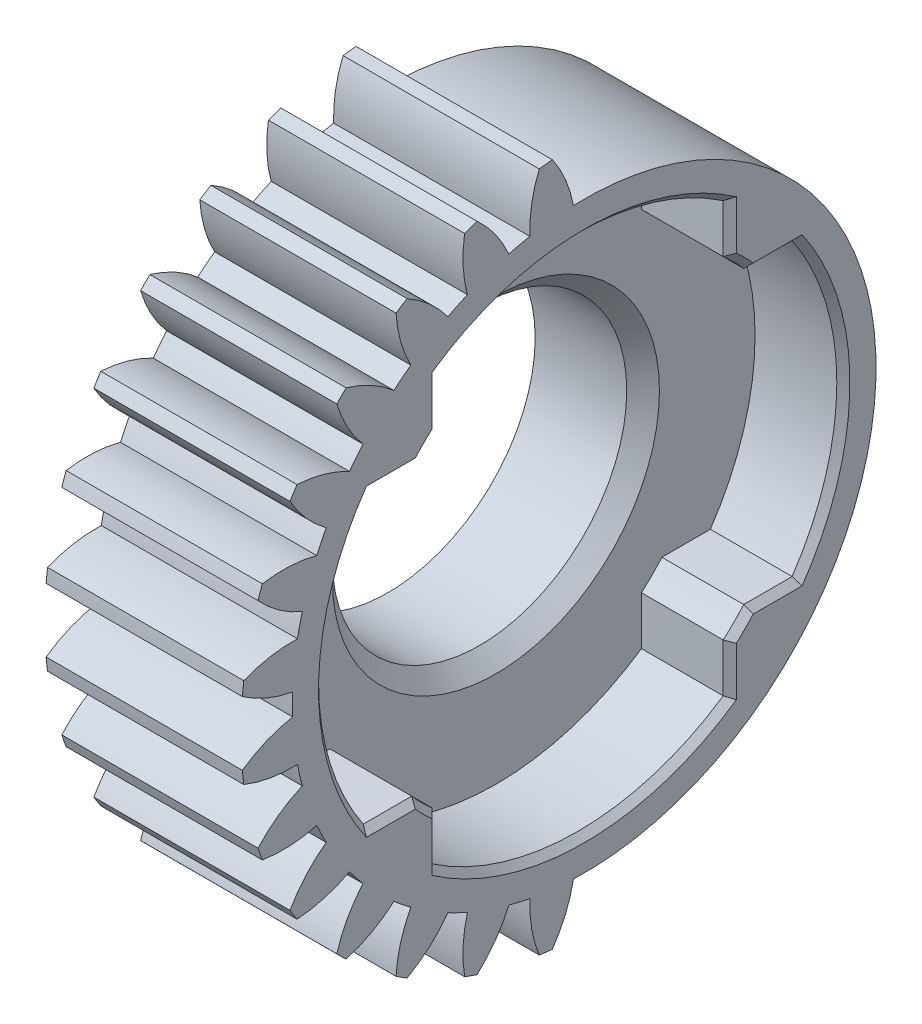
SolidWorks part; units mm, degrees
ref_plane "Plane1" through (0, 0, 0) normal (0, 0, 1) x (1, 0, 0)
ref_plane "Plane2" through (0, 0, 0) normal (0, 1, 0) x (1, 0, 0)
ref_plane "Plane3" through (0, 0, 0) normal (1, 0, 0) x (0, 0, -1)
sketch "HoldingSke" plane through (0, 0, 0) normal (0, 1, 0) x (1, 0, 0)
  line L0 (0, 0) -> (1.2614, -0.6707)
  line L1 (-15, 0) -> (100, 0) construction
  line L2 (0, 0) -> (-2.1039, 2.3779)
  line L3 (0, 0) -> (-11.863, 4.5341)
  line L4 (0, 0) -> (7.6251, 4.0544)
  line L5 (0, 0) -> (-46.8476, -17.4728)
  line L6 (0, 0) -> (-4.9738, -3.3558)
  line L7 (-2.1039, 2.3779) -> (8.6586, 51.2059)
  line L8 (-76.2, 54.61) -> (-75.7, 54.61)
  line L9 (-71.009, 38.7566) -> (-53.1078, 45.2721)
  line L10 (-76.2, 71.12) -> (104.1128, 71.12)
  line L11 (0, 0) -> (-6, 0)
  line L12 (-76.2, 101.6) -> (-76.173, 101.6)
  line L13 (24.9733, 27.94) -> (52.9518, 28.4284)
  line L14 (24.9733, 27.94) -> (24.9743, 27.94)
  line L15 (24.9733, 27.94) -> (100.4006, 29.5858)
  line L16 (-63.627, -0.7) -> (-12.827, -0.7)
  circle A0 centre (0, 0) radius 1.5
  circle A1 centre (0, 0) radius 8.924
  circle A2 centre (0, 0) radius 37.5
  circle A3 centre (0, 0) radius 1.5
  dimension "MHD" = 17.848
  dimension "Hub_dia" = 75
  dimension "Bore" = 3
  dimension "MBD" = 3
  dimension "Num_teeth" = 28
  dimension "Pitch" = 1.4286
  dimension "Overall_len" = 50
  dimension "Show_teeth" = 28
  dimension "Thickness" = 6
  dimension "OAL" = 50.0001
  dimension "T_dim" = 0.5
  dimension "Ap" = 20
  dimension "H" = 19.05
  dimension "Pitch_radius" = 180.3128
  dimension "Width" = 6
  dimension "Backlash" = 0.027
  dimension "Addendum_fac" = 1
  dimension "Dedendum_fac" = 1.25
  dimension "Clearance_fac" = 0.25
  dimension "Dedendum_add" = 0.001
  dimension "Module" = 0.7
sketch "BasProSke" plane through (0, 0, 0) normal (0, 1, 0) x (1, 0, 0)
  line L0 (-10, 0) -> (60, 0) construction
  line L1 (0, 0) -> (0, 10.5)
  line L2 (0, 0) -> (6, 0)
  line L3 (6, 0) -> (6, 10.5)
  line L4 (6, 10.5) -> (0, 10.5)
  dimension "Thickness" = 6
  dimension "Diameter" = 21
revolve "Base-Revolve" add sketch "BasProSke" angle 360 about L0
sketch "TooCutSke" plane through (0, 0, 0) normal (1, 0, 0) x (0, 0, -1)
  line L1 (0, 0) -> (0, 107) construction
  line L2 (0, 0) -> (-0.5967, 9.7818) construction
  line L3 (0, 0) -> (-2.1916, 19.4512) construction
  line L4 (-0.5967, 9.7818) -> (-1.0958, 9.7256) construction
  arc A0 (0.3305, 8.9179) -> (-0.3305, 8.9179) centre (0, 0) ccw
  arc A1 (0.9927, 10.4785) -> (-0.9927, 10.4785) centre (0, 0) ccw
  circle A2 centre (0, 0) radius 9.8 construction
  circle A3 centre (0, 0) radius 9.209 construction
  arc A4 (-0.3305, 8.9179) -> (-0.9927, 10.4785) centre (-4.1848, 8.2032) ccw
  arc A5 (0.9927, 10.4785) -> (0.3305, 8.9179) centre (4.1848, 8.2032) ccw
  dimension "Root_dia" = 17.848
  dimension "Overcut_dia" = 21.0508
  dimension "Pitch_dia" = 19.6
  dimension "Base_dia" = 18.418
  dimension "Flank_rad" = 3.92
  dimension "Half_ang" = 6.429
  dimension "Half_CT" = 0.5022
extrude "ToothCut" cut sketch "TooCutSke" along normal through all
fillet "Breaks" [suppressed] radius 0.014
fillet "RootFillets" [suppressed] radius 0.176
pattern_circular "TeethCuts" count 28 every 12.857 about axis through (-10, 0, 0) along (1, 0, 0) of "ToothCut", "RootFillets", "Breaks"
sketch "HubNeaOneSke" plane through (0, 0, 0) normal (-1, 0, 0) x (0, 0, 1)
  circle A0 centre (0, 0) radius 8.924
  dimension "Diameter" = 17.848
extrude "HubNearOne" [suppressed] add sketch "HubNeaOneSke" along normal blind 44.0001
sketch "HubNeaBotSke" plane through (0, 0, 0) normal (-1, 0, 0) x (0, 0, 1)
  circle A0 centre (0, 0) radius 8.924
  dimension "Diameter" = 17.848
extrude "HubNearBoth" [suppressed] add sketch "HubNeaBotSke" along normal blind 22
ref_plane "FarPln" through (6, 0, 0) normal (1, 0, 0) x (0, 0, -1)
sketch "HubFarSke" plane through (6, 0, 0) normal (1, 0, 0) x (0, 0, -1)
  circle A0 centre (0, 0) radius 8.924
  dimension "Diameter" = 17.848
extrude "HubFar" [suppressed] add sketch "HubFarSke" along normal blind 22
sketch "BorSke" plane through (0, 0, 0) normal (1, 0, 0) x (0, 0, -1)
  circle A0 centre (0, 0) radius 1.5
  dimension "Diameter" = 3
extrude "Bore" cut sketch "BorSke" along normal mid plane 100.0001
sketch "KeySke" plane through (0, 0, 0) normal (1, 0, 0) x (0, 0, -1)
  line L0 (-0.6, 0) -> (-0.6, 2)
  line L1 (-0.6, 2) -> (0.6, 2)
  line L2 (0.6, 2) -> (0.6, 0)
  line L3 (0, 0) -> (0, 34) construction
  line L4 (-0.6, 0) -> (0.6, 0)
  dimension "Offset" = 2
  dimension "Width" = 1.2
extrude "Keyway" [suppressed] cut sketch "KeySke" along normal mid plane 100.0001
pattern_circular "Keyway2" [suppressed] count 2 every 90 about axis through (-10, 0, 0) along (1, 0, 0)
sketch "Szkic1" plane through (6, 0, 0) normal (1, 0, 0) x (0, 0, -1)
  circle A0 centre (0, 0) radius 6.75
  dimension "D1" = 13.5
extrude "Wytnij-wyciągnięcie1" cut sketch "Szkic1" against normal blind 2.7
sketch "Szkic2" plane through (3.3, 0, 0) normal (1, 0, 0) x (0, 0, -1)
  circle A0 centre (0, 0) radius 4.5
  dimension "D1" = 9
extrude "Wytnij-wyciągnięcie2" cut sketch "Szkic2" against normal through all
sketch "Szkic3" plane through (6, 0, 0) normal (1, 0, 0) x (0, 0, -1)
  line L1 (6.5565, -4.45) -> (-6.5565, -4.45)
  line L2 (6.5565, -4.45) -> (6.5565, 4.45)
  line L3 (6.5565, 4.45) -> (-6.5565, 4.45)
  line L4 (-6.5565, -4.45) -> (-6.5565, 4.45)
  line L5 (6.5565, -4.45) -> (-6.5565, 4.45) construction
  line L6 (6.5565, 4.45) -> (-6.5565, -4.45) construction
  line L7 (4.45, -6.5565) -> (-4.45, -6.5565)
  line L8 (4.45, -6.5565) -> (4.45, 6.5565)
  line L9 (4.45, 6.5565) -> (-4.45, 6.5565)
  line L10 (-4.45, -6.5565) -> (-4.45, 6.5565)
  line L11 (4.45, -6.5565) -> (-4.45, 6.5565) construction
  line L12 (4.45, 6.5565) -> (-4.45, -6.5565) construction
  circle A0 centre (0, 0) radius 7.924
  arc A1 (-1.6622, 8.7678) -> (-2.3066, 8.6207) centre (0, 0) ccw construction
  dimension "D1" = 1
  dimension "D2" = 8.9
extrude "Wytnij-wyciągnięcie3" cut sketch "Szkic3" against normal up to surface (2.7 mm away) contours L10 L3 L8 L9 | L1 L10 L3 L4 | L4 A0 | L9 A0 | L2 A0 | L8 L1 L2 L3 | L7 A0 | L10 L7 L8 L1 up to face at (3.3, 0, -4.5)
sketch "Szkic4" plane through (3.3, 0, 0) normal (1, 0, 0) x (0, 0, -1)
  line L0 (0, 10.924) -> (0, 8.924)
  line L1 (0, -8.924) -> (0, -10.924)
  arc A0 (0, 8.924) -> (0, -8.924) centre (0, 0) cw
  arc A1 (0.3305, 8.9179) -> (-0.3305, 8.9179) centre (0, 0) ccw construction
  arc A2 (0, 10.924) -> (0, -10.924) centre (0, 0) cw
  arc A3 (-0.3305, -8.9179) -> (0.3305, -8.9179) centre (0, 0) ccw construction
  dimension "D1" = 2
extrude "Wytnij-wyciągnięcie4" cut sketch "Szkic4" against normal through all and the other way through all
chamfer "Sfazowanie1" distance 0.2 angle 45 16 edges at (6, 5.8159, -4.45) (6, -5.8159, -4.45) (6, 4.773, -4.773) (6, 4.45, 5.8159) (6, 4.45, -5.8159) (6, 0, 7.924) (6, 0, -7.924) (6, -4.45, 5.8159) (6, -4.45, -5.8159) (6, -4.773, -4.773) (6, 7.924, 0) (6, -7.924, 0) (6, -5.8159, 4.45) (6, 5.8159, 4.45) (6, -4.773, 4.773) (6, 4.773, 4.773)
chamfer "Sfazowanie2" distance 0.5 angle 45 1 edges at (3.3, 0, -4.5)
equation "' \"Module@HoldingSke\" = 6.35"
equation "' \"Num_teeth@HoldingSke\" = 12"
equation "' \"Ap@HoldingSke\" =  20"
equation "' \"Ap@HoldingSke\" = 20"
equation "' \"Width@HoldingSke\" = 0.5 * 25.4"
equation "' \"Hub_dia@HoldingSke\"= 1 * 25.4"
equation "' \"Hub_dia@HoldingSke\" = 1 * 25.4"
equation "' \"Overall_len@HoldingSke\" = 1.0 * 25.4"
equation "' \"Bore@HoldingSke\" = 0.75 * 25.4"
equation "' \"T_dim@HoldingSke\" = 0.1 * 25.4"
equation "' \"Width@KeySke\" = 0.25 * 25.4"
equation "' \"Show_teeth@HoldingSke\" = 13"
equation "' \"Backlash@HoldingSke\" = 0.009 * 25.4"
equation "' \"Addendum_fac@HoldingSke\" = 1.0"
equation "' \"Dedendum_fac@HoldingSke\" = 1.25"
equation "' \"Dedendum_add@HoldingSke\" = 0.00005 * 25.4"
equation "' \"Clearance_fac@HoldingSke\" = 0.25"
equation "\"Pitch@HoldingSke\" = 1 / \"Module@HoldingSke\""
equation "\"Overcut_dia@TooCutSke\" = (\"Num_teeth@HoldingSke\" + 2 * \"Addendum_fac@HoldingSke\") / \"Pitch@HoldingSke\" + 0.002 * 25.4"
equation "\"Pitch_dia@TooCutSke\" = \"Num_teeth@HoldingSke\" / \"Pitch@HoldingSke\""
equation "\"Base_dia@TooCutSke\" = \"Num_teeth@HoldingSke\" / \"Pitch@HoldingSke\" * cos((\"Ap@HoldingSke\"  * 3.14159265 / 180))"
equation "\"Root_dia@TooCutSke\" = (\"Num_teeth@HoldingSke\" + 2) / \"Pitch@HoldingSke\" - 2 * (\"Addendum_fac@HoldingSke\" + \"Dedendum_fac@HoldingSke\") / \"Pitch@HoldingSke\" - \"Dedendum_add@HoldingSke\" * 2"
equation "\"Half_ang@TooCutSke\" = 180 / \"Num_teeth@HoldingSke\""
equation "\"Half_CT@TooCutSke\" = \"Num_teeth@HoldingSke\" / \"Pitch@HoldingSke\" * sin((3.14159265 / 2 / \"Num_teeth@HoldingSke\")) / 2 - 7 * \"Backlash@HoldingSke\" / 4"
equation "\"Flank_rad@TooCutSke\" = \"Num_teeth@HoldingSke\" / \"Pitch@HoldingSke\" / 5"
equation "\"Radius@RootFillets\" = \"Clearance_fac@HoldingSke\" / \"Pitch@HoldingSke\" + \"Dedendum_add@HoldingSke\""
equation "\"Break_rad@Breaks\" = 0.02 / \"Pitch@HoldingSke\""
equation "\"Thickness@HoldingSke\" = \"Width@HoldingSke\""
equation "\"OAL@HoldingSke\" = \"Thickness@HoldingSke\""
equation "\"MHD@HoldingSke\" = (\"Num_teeth@HoldingSke\" + 2) / \"Pitch@HoldingSke\" - 2 * (\"Addendum_fac@HoldingSke\" + \"Dedendum_fac@HoldingSke\")  / \"Pitch@HoldingSke\" - \"Dedendum_add@HoldingSke\" * 2"
equation "\"MBD@HoldingSke\" = (\"Num_teeth@HoldingSke\" + 2) / \"Pitch@HoldingSke\" - 2 * (\"Addendum_fac@HoldingSke\" + \"Dedendum_fac@HoldingSke\")  / \"Pitch@HoldingSke\" - \"Dedendum_add@HoldingSke\" * 2 - 0.002 * 25.4"
equation "\"MHD@HoldingSke\" = ((sgn( \"MHD@HoldingSke\" - \"Hub_dia@HoldingSke\" )-1)*( \"MHD@HoldingSke\" - \"Hub_dia@HoldingSke\" ))/-2+ \"Hub_dia@HoldingSke\""
equation "\"MBD@HoldingSke\" = ((sgn( \"MBD@HoldingSke\" - \"Bore@HoldingSke\" )-1)*( \"MBD@HoldingSke\" - \"Bore@HoldingSke\" ))/-2+ \"Bore@HoldingSke\""
equation "\"OAL@HoldingSke\" = ((sgn( \"OAL@HoldingSke\" - \"Overall_len@HoldingSke\" )+1)*( \"OAL@HoldingSke\" - \"Overall_len@HoldingSke\" ))/2 + \"Overall_len@HoldingSke\" + 0.000002 * 25.4"
equation "\"Num_teeth@TeethCuts\" = int( \"Show_teeth@HoldingSke\" ) + 1"
equation "\"Num_teeth@TeethCuts\" = ((sgn( \"Num_teeth@TeethCuts\" - \"Num_teeth@HoldingSke\" )-1)*( \"Num_teeth@TeethCuts\" - \"Num_teeth@HoldingSke\" ))/-2+ \"Num_teeth@HoldingSke\""
equation "\"Num_teeth@TeethCuts\" = ((sgn( \"Num_teeth@TeethCuts\" - 2.0)+1)*( \"Num_teeth@TeethCuts\" - 2.0))/2 +2.0"
equation "\"Angle@TeethCuts\" = 360.0 / \"Num_teeth@HoldingSke\""
equation "\"Diameter@BasProSke\" = (\"Num_teeth@HoldingSke\" + 2 * \"Addendum_fac@HoldingSke\") / \"Pitch@HoldingSke\""
equation "\"Thickness@BasProSke\"  = \"Thickness@HoldingSke\""
equation "' \"Fillet_rad@BasProSke\" =  \"Thickness@HoldingSke\" * 0.05"
equation "' \"Fillet_rad@BasProSke\" = \"Thickness@HoldingSke\" * 0.05"
equation "\"MHD@HoldingSke\" = ((sgn( \"MHD@HoldingSke\" - \"Root_dia@TooCutSke\" )-1)*( \"MHD@HoldingSke\" - \"Root_dia@TooCutSke\" ))/-2+ \"Root_dia@TooCutSke\""
equation "\"Diameter@HubNeaOneSke\" = \"MHD@HoldingSke\""
equation "\"Length@HubNearOne\" = \"OAL@HoldingSke\" - \"Thickness@BasProSke\""
equation "\"Diameter@HubNeaBotSke\" = \"MHD@HoldingSke\""
equation "\"Length@HubNearBoth\" = ( \"OAL@HoldingSke\" - \"Thickness@BasProSke\" ) / 2.0"
equation "\"Thickness@FarPln\" = \"Thickness@BasProSke\""
equation "\"Diameter@HubFarSke\" = \"MHD@HoldingSke\""
equation "\"Length@HubFar\" = ( \"OAL@HoldingSke\" - \"Thickness@BasProSke\" ) / 2.0"
equation "\"Diameter@BorSke\" = \"MBD@HoldingSke\""
equation "\"D1@Bore\" = \"OAL@HoldingSke\" * 2.0"
equation "\"D1@Keyway\" = \"OAL@HoldingSke\" * 2.0"
equation "\"Offset@KeySke\" = \"T_dim@HoldingSke\" + \"MBD@HoldingSke\" / 2.0"
